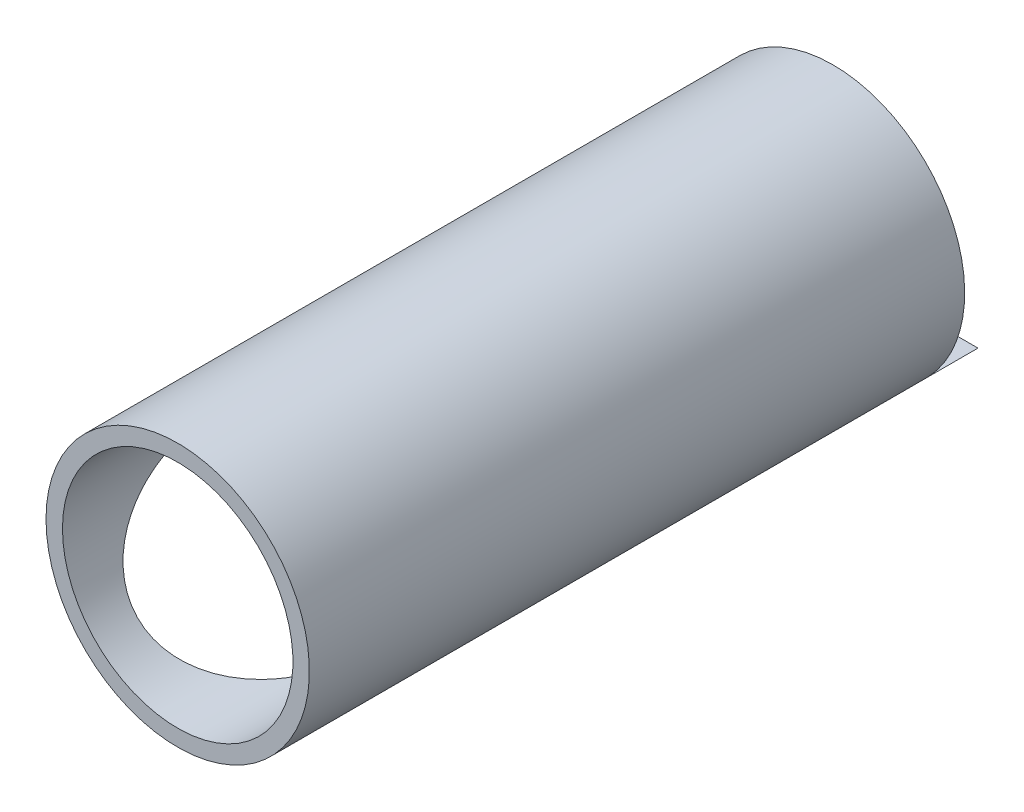
SolidWorks part; units mm, degrees
material "Acrylic (Medium-high impact)"
ref_plane "Front Plane" through (0, 0, 0) normal (0, 0, 1) x (1, 0, 0)
ref_plane "Top Plane" through (0, 0, 0) normal (0, 1, 0) x (1, 0, 0)
ref_plane "Right Plane" through (0, 0, 0) normal (1, 0, 0) x (0, 0, -1)
sketch "Sketch1" plane through (0, 0, 0) normal (0, 0, 1) x (1, 0, 0)
  circle A0 centre (0, 0) radius 25.4
  circle A1 centre (0, 0) radius 22.225
  dimension "D1" = 50.8
  dimension "D2" = 44.45
extrude "Boss-Extrude1" add sketch "Sketch1" along normal blind 914.4
sketch "Sketch2" plane through (0, 0, 0) normal (0, 0, -1) x (-1, 0, 0)
  circle A0 centre (0, 0) radius 25.4 construction
  circle A1 centre (0, 0) radius 25.4
extrude "Cut-Extrude1" cut sketch "Sketch2" against normal through all from offset 152.4 offset against normal yes
ref_plane "Plane1" through (0, -25.4, 0) normal (0, -1, 0) x (-1, 0, 0)
ref_plane "Plane3" through (0, -22.225, 0) normal (0, 1, 0) x (1, 0, 0)
ref_plane "Plane2" through (0, 0, 9.525) normal (0, 0, -1) x (-1, 0, 0)
sketch "Sketch3" plane through (0, 0, 9.525) normal (0, 0, -1) x (-1, 0, 0)
  line L0 (-18.4451, -17.4625) -> (18.4451, -17.4625)
  line L1 (0, -17.4625) -> (0, -25.4) construction
  circle A0 centre (0, 0) radius 25.4 construction
  arc A1 (18.4451, -17.4625) -> (-18.4451, -17.4625) centre (0, 0) ccw
  dimension "D1" = 7.9375
extrude "Cut-Extrude2" cut sketch "Sketch3" along normal through all
ref_plane "Plane4" through (0, 25.4, 0) normal (0, 1, 0) x (1, 0, 0)
sketch "Sketch4" plane through (0, 25.4, 0) normal (0, 1, 0) x (1, 0, 0)
  line L1 (-25.4, -9.525) -> (-25.4, -152.4) construction
  line L2 (25.4, -152.4) -> (25.4, -9.525) construction
  line L3 (-25.4, -135.9131) -> (25.4, -135.9131)
  line L4 (-25.4, -135.9131) -> (-25.4, -152.4)
  line L5 (-25.4, -152.4) -> (25.4, -152.4)
  line L6 (25.4, -152.4) -> (25.4, -135.9131)
  line L7 (-25.4, -152.4) -> (25.4, -152.4) construction
  dimension "D1" = 16.4869
extrude "Cut-Extrude3" cut sketch "Sketch4" against normal through all
ref_plane "Plane5" through (-17.9605, -17.9605, 0) normal (-0.7071, -0.7071, 0) x (0, 0, -1)
sketch "Sketch5" plane through (-17.9605, -17.9605, 0) normal (-0.7071, -0.7071, 0) x (0, 0, -1)
  line L0 (-135.9131, 25.4) -> (-135.9131, -25.4) construction
  line L1 (108.8476, 0) -> (-108.8476, 0)
  line L2 (-108.8476, 0) -> (-127.8976, 0) construction
  line L3 (-127.8976, 0) -> (-135.9131, 0) construction
  line L4 (-135.9131, 22.225) -> (-135.9131, -22.225) construction
  circle A0 centre (-108.8476, 0) radius 19.05
  point P12 (0, 0)
  dimension "D1" = 38.1
  dimension "D2" = 27.0655
extrude "Cut-Extrude4" cut sketch "Sketch5" against normal up to surface (13.9524 mm away)
